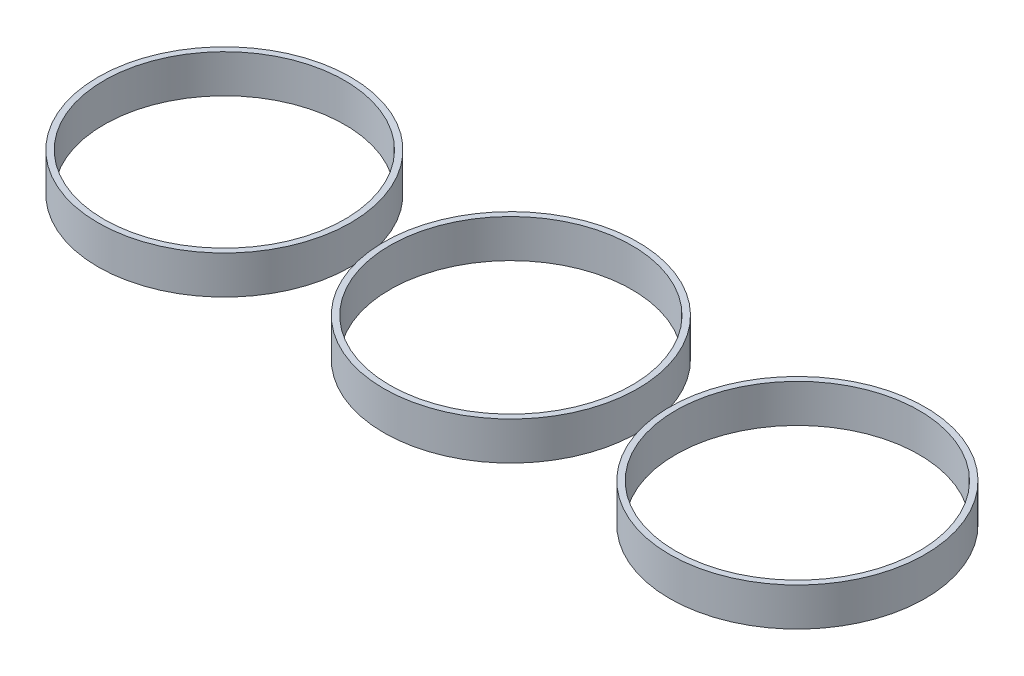
SolidWorks part; units mm, degrees
ref_plane "Front Plane" through (0, 0, 0) normal (0, 0, 1) x (1, 0, 0)
ref_plane "Top Plane" through (0, 0, 0) normal (0, 1, 0) x (1, 0, 0)
ref_plane "Right Plane" through (0, 0, 0) normal (1, 0, 0) x (0, 0, -1)
sketch "Sketch2" plane through (0, 0, 0) normal (0, 1, 0) x (1, 0, 0)
  circle A0 centre (0, 0) radius 26.45
  dimension "D1" = 52.9
extrude "Boss-Extrude1" add sketch "Sketch2" along normal blind 8
sketch "Sketch3" plane through (0, 8, 0) normal (0, 1, 0) x (1, 0, 0)
  circle A0 centre (0, 0) radius 25.2
  dimension "D1" = 50.4
extrude "Cut-Extrude1" cut sketch "Sketch3" against normal through all both and the other way through all
sketch "Sketch5" plane through (0, 0, 0) normal (0, 1, 0) x (1, 0, 0)
  circle A0 centre (60, 0) radius 26.6
  circle A1 centre (0, 0) radius 26.45 construction
  point P2 (0, 0)
  point P3 (0, 0)
  dimension "D1" = 53.2
  dimension "D2" = 60
extrude "Boss-Extrude2" add sketch "Sketch5" along normal blind 8 separate body
sketch "Sketch6" plane through (0, 8, 0) normal (0, 1, 0) x (1, 0, 0)
  circle A0 centre (60, 0) radius 25.35
  dimension "D1" = 50.7
extrude "Cut-Extrude2" cut sketch "Sketch6" against normal through all both and the other way through all
sketch "Sketch7" plane through (0, 0, 0) normal (0, 1, 0) x (1, 0, 0)
  circle A0 centre (120, 0) radius 26.75
  circle A1 centre (60, 0) radius 26.6 construction
  point P2 (0, 0)
  dimension "D1" = 53.5
  dimension "D2" = 60
extrude "Boss-Extrude3" add sketch "Sketch7" along normal blind 8 separate body
sketch "Sketch8" plane through (0, 8, 0) normal (0, 1, 0) x (1, 0, 0)
  circle A0 centre (120, 0) radius 25.5
  dimension "D1" = 51
extrude "Cut-Extrude3" cut sketch "Sketch8" against normal through all both and the other way through all
